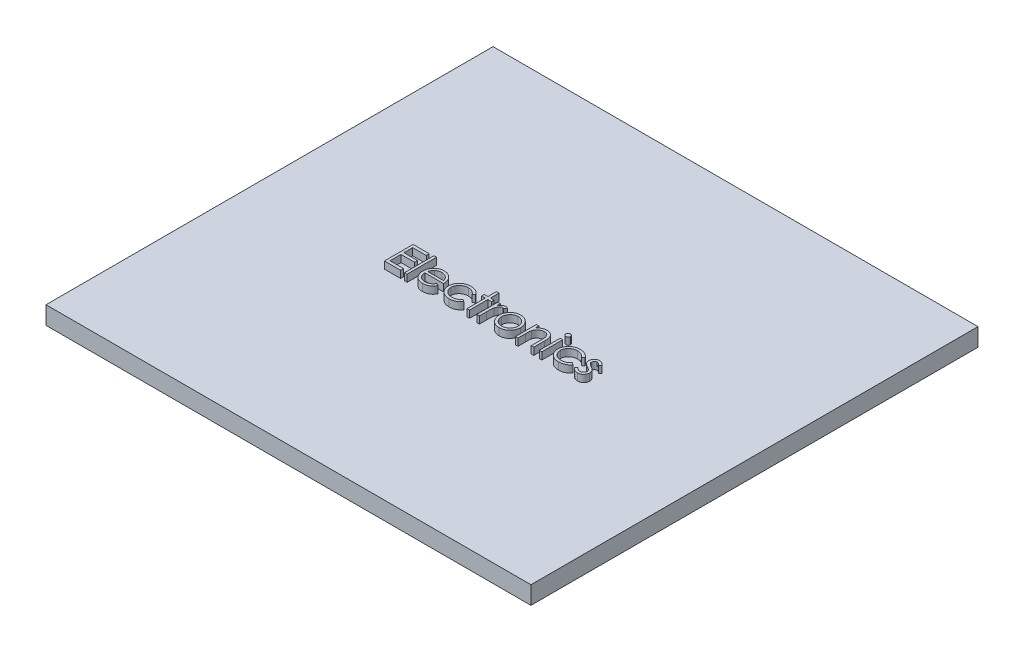
SolidWorks part; units mm, degrees
ref_plane "Front Plane" through (0, 0, 0) normal (0, 0, 1) x (1, 0, 0)
ref_plane "Top Plane" through (0, 0, 0) normal (0, 1, 0) x (1, 0, 0)
ref_plane "Right Plane" through (0, 0, 0) normal (1, 0, 0) x (0, 0, -1)
sketch "Sketch1" plane through (0, 0, 0) normal (0, 1, 0) x (1, 0, 0)
  line L1 (0, 0) -> (86.106, 0)
  line L2 (0, 0) -> (0, 79.375)
  line L3 (0, 79.375) -> (86.106, 79.375)
  line L4 (86.106, 0) -> (86.106, 79.375)
  dimension "D1" = 79.375
  dimension "D2" = 86.106
extrude "Boss-Extrude1" add sketch "Sketch1" along normal blind 3.175
sketch "Sketch2" plane through (0, 3.175, 0) normal (0, 1, 0) x (1, 0, 0)
  text T0 "Electronics" font "Century Gothic" height 5.08
extrude "Boss-Extrude2" add sketch "Sketch2" along normal blind 1.27
